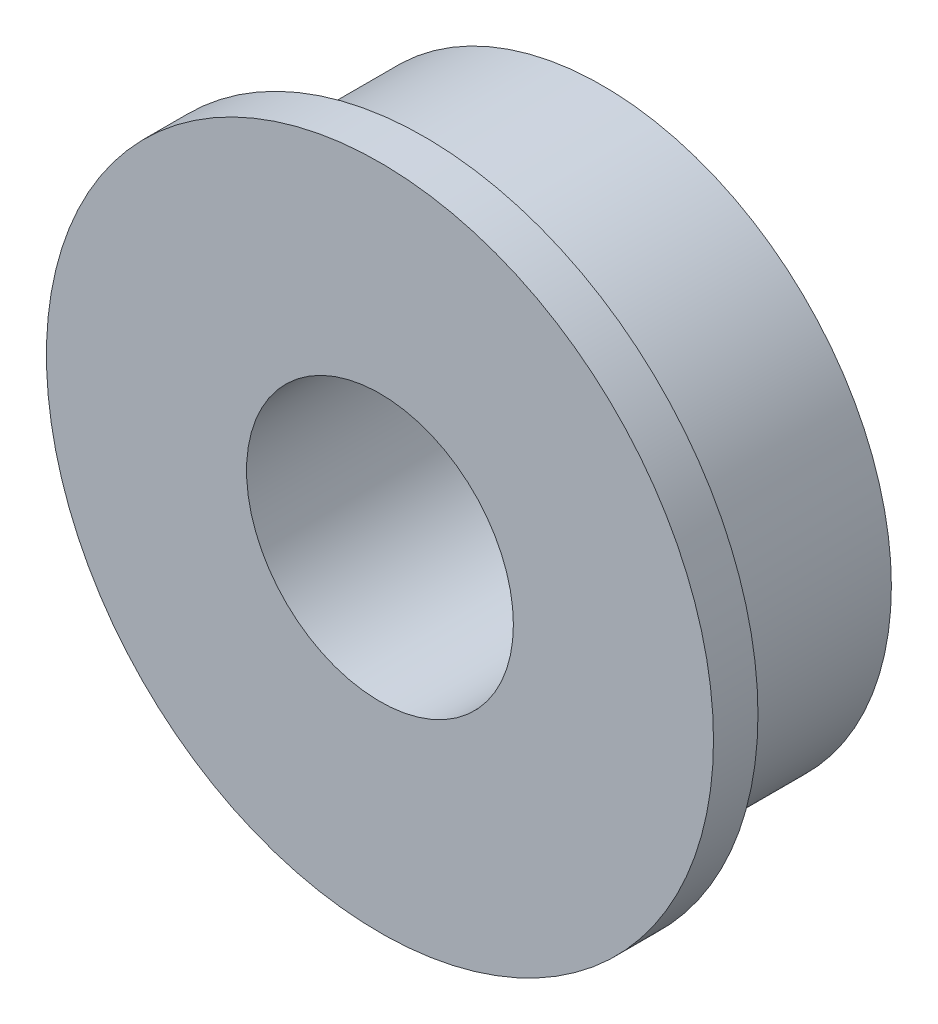
SolidWorks part; units mm, degrees
ref_plane "Front Plane" through (0, 0, 0) normal (0, 0, 1) x (1, 0, 0)
ref_plane "Top Plane" through (0, 0, 0) normal (0, 1, 0) x (1, 0, 0)
ref_plane "Right Plane" through (0, 0, 0) normal (1, 0, 0) x (0, 0, -1)
sketch "Sketch1" plane through (0, 0, 0) normal (1, 0, 0) x (0, 0, -1)
  line L0 (0, 3) -> (0, 7.5)
  line L1 (0, 7.5) -> (1, 7.5)
  line L2 (1, 7.5) -> (1, 6.5)
  line L3 (1, 6.5) -> (5, 6.5)
  line L4 (5, 6.5) -> (5, 3)
  line L5 (5, 3) -> (0, 3)
  line L6 (0, 0) -> (9.6313, 0) construction
  dimension "D1" = 3
  dimension "D2" = 5
  dimension "D3" = 7.5
  dimension "D4" = 1
  dimension "D5" = 1
revolve "Revolve1" add sketch "Sketch1" angle 360 about L6
